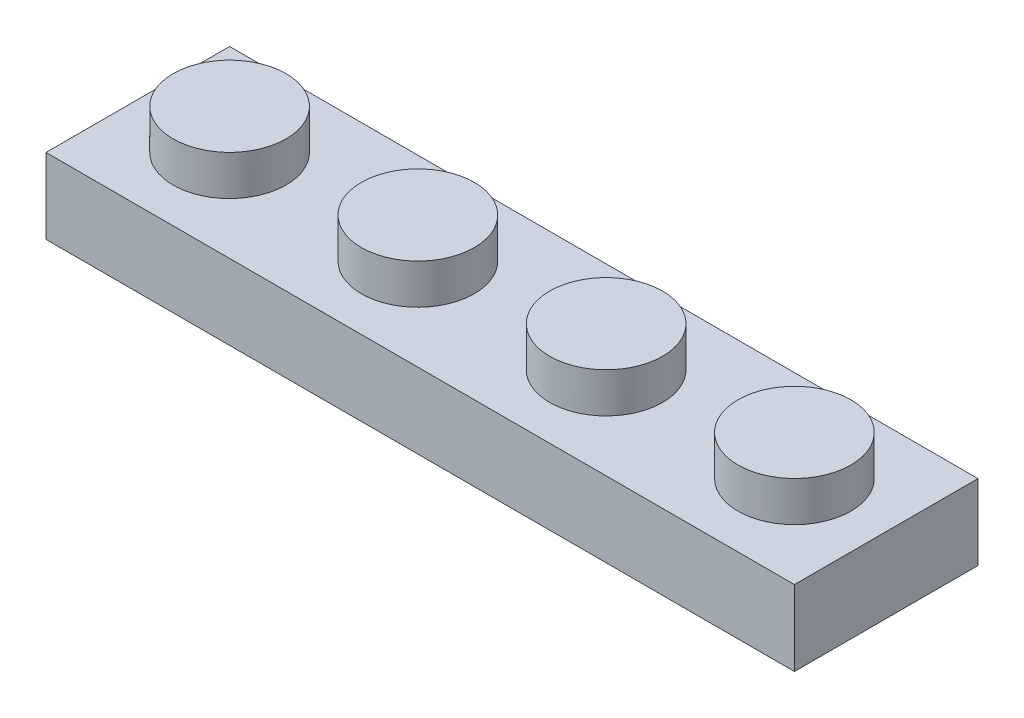
SolidWorks part; units mm, degrees
ref_plane "Front Plane" through (0, 0, 0) normal (0, 0, 1) x (1, 0, 0)
ref_plane "Top Plane" through (0, 0, 0) normal (0, 1, 0) x (1, 0, 0)
ref_plane "Right Plane" through (0, 0, 0) normal (1, 0, 0) x (0, 0, -1)
sketch "Base_Sketch" plane through (0, 0, 0) normal (0, 1, 0) x (1, 0, 0)
  line L1 (0, 0) -> (31.8, 0)
  line L2 (0, 0) -> (0, 7.8)
  line L3 (0, 7.8) -> (31.8, 7.8)
  line L4 (31.8, 0) -> (31.8, 7.8)
  dimension "Brick_Length" = 31.8
  dimension "Brick_Width" = 7.8
extrude "Base_Brick" add sketch "Base_Sketch" along normal blind 3.2
sketch "Circle_Sketch" plane through (0, 3.2, 0) normal (0, 1, 0) x (1, 0, 0)
  line L0 (0, 7.8) -> (0, 0) construction
  line L1 (0, 0) -> (31.8, 0) construction
  circle A0 centre (3.9, 3.9) radius 2.4
  dimension "R" = 4.8
  dimension "D1" = 3.9
  dimension "ED" = 3.9
extrude "Circle" add sketch "Circle_Sketch" along normal blind 1.7 contours A0
pattern_linear "LPattern1" count 4 spacing 8 along (1, 0, 0) of "Circle"
equation "\"P\"= 8.0"
equation "\"h\"= 0.4 * \"P\""
equation "\"w\"= \"P\" - 0.2"
equation "\"L\"= 2 * \"P\" - 0.2"
equation "\"R\"= 4.8"
equation "\"T\"= 1.7"
equation "\"D\"= 3.2"
equation "\"Hi\"= 1.2 * \"P\""
equation "\"Ed\"= \"D\" / 2 + \"R\" / 2 - 0.1"
equation "\"X\"= 2"
equation "\"Y\"= 1"
equation "\"CD\"= \"D\" + \"R\""
